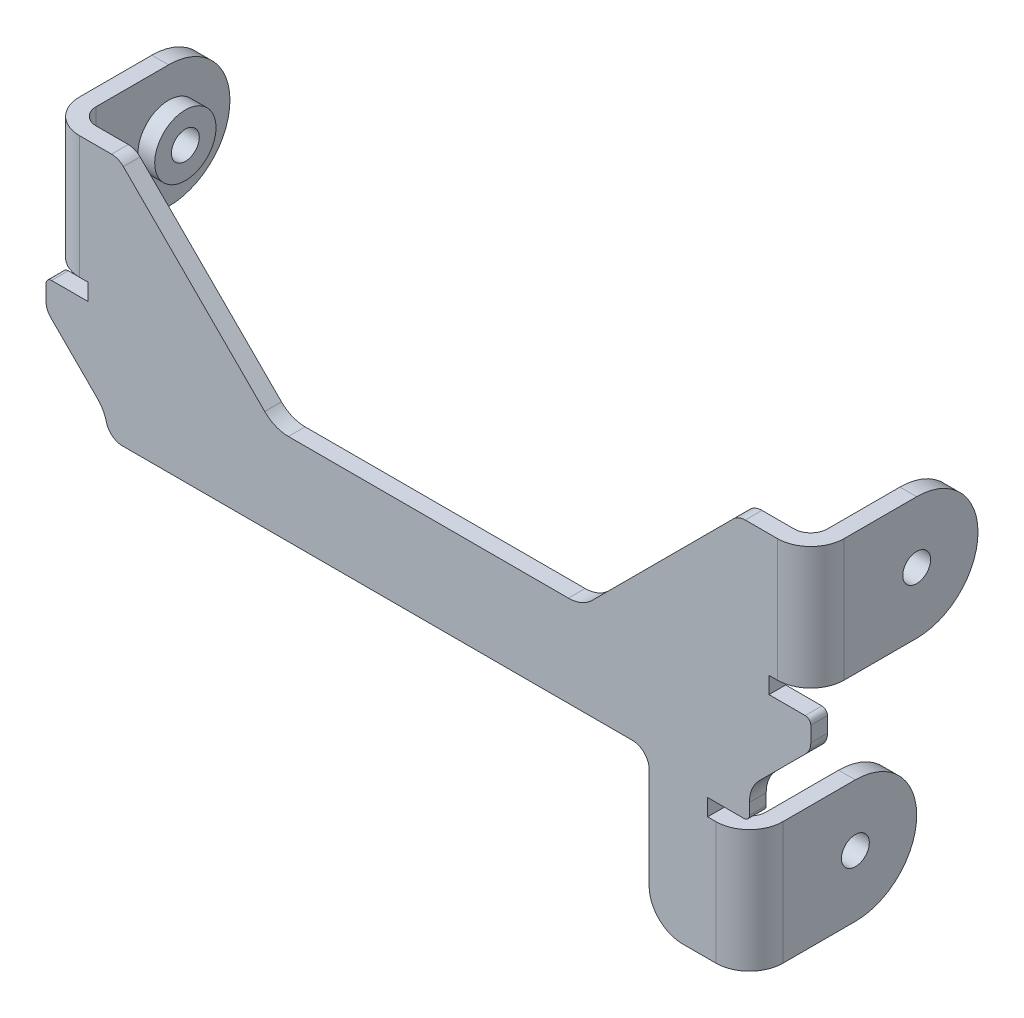
SolidWorks part; units mm, degrees
ref_plane "前视基准面" through (0, 0, 0) normal (0, 0, 1) x (1, 0, 0)
ref_plane "上视基准面" through (0, 0, 0) normal (0, 1, 0) x (1, 0, 0)
ref_plane "右视基准面" through (0, 0, 0) normal (1, 0, 0) x (0, 0, -1)
sketch "草图1" plane through (0, 0, 0) normal (0, 0, 1) x (1, 0, 0)
  line L0 (-11.75, 37) -> (-11.75, 24.7574)
  line L1 (-11.75, 24.7574) -> (-6.25, 24.7574)
  line L2 (-6.25, 24.7574) -> (-6.25, 37)
  line L3 (-6.25, 37) -> (-11.75, 37)
extrude "凸台-拉伸1" add sketch "草图1" against normal blind 1.5
sketch "草图2" plane through (-11.75, 0, 0) normal (-1, 0, 0) x (0, 0, 1)
  line L0 (0, 37) -> (0, 12.2574)
  line L1 (0, 12.2574) -> (-1.5, 12.2574)
  line L2 (-1.5, 12.2574) -> (-1.5, 37)
  line L3 (-1.5, 37) -> (0, 37)
extrude "凸台-拉伸2" add sketch "草图2" along normal blind 55.6
sketch "草图3" plane through (-11.75, 0, 0) normal (1, 0, 0) x (0, 0, -1)
  line L0 (0, 23.2574) -> (1.5, 23.2574)
  line L1 (1.5, 23.2574) -> (1.5, 12.2574)
  line L2 (1.5, 12.2574) -> (0, 12.2574)
  line L3 (0, 12.2574) -> (0, 23.2574)
extrude "凸台-拉伸3" add sketch "草图3" along normal blind 2.25
sketch "草图4" plane through (0, 37, 0) normal (0, 1, 0) x (-1, 0, 0)
  line L0 (4, 0) -> (67.35, 0)
  line L1 (67.35, 0) -> (67.35, -1.5)
  line L2 (67.35, -1.5) -> (4, -1.5)
  line L3 (4, -1.5) -> (4, 0)
extrude "凸台-拉伸4" add sketch "草图4" along normal blind 11
sketch "草图5" plane through (-4, 0, 0) normal (1, 0, 0) x (0, 0, -1)
  line L0 (0, 48) -> (9.5, 48)
  line L1 (9.5, 37) -> (0, 37)
  line L2 (0, 37) -> (0, 48)
  arc A0 (9.5, 48) -> (9.5, 37) centre (9.5, 42.5) cw
extrude "凸台-拉伸5" add sketch "草图5" along normal blind 1.5
sketch "草图6" plane through (-9.5, 0, 0) normal (1, 0, 0) x (0, 0, -1)
  line L0 (9.5, 12.2574) -> (0, 12.2574)
  line L1 (0, 12.2574) -> (0, 23.2574)
  line L2 (0, 23.2574) -> (9.5, 23.2574)
  arc A0 (9.5, 23.2574) -> (9.5, 12.2574) centre (9.5, 17.7574) cw
extrude "凸台-拉伸6" add sketch "草图6" along normal blind 1.5
sketch "草图7" plane through (-67.35, 0, 0) normal (-1, 0, 0) x (0, 0, 1)
  line L0 (0, 37) -> (-1.5, 37)
  line L1 (-1.5, 37) -> (-1.5, 48)
  line L2 (-1.5, 48) -> (0, 48)
  line L3 (0, 48) -> (0, 37)
extrude "凸台-拉伸7" add sketch "草图7" along normal blind 2.25
sketch "草图8" plane through (-69.6, 0, 0) normal (-1, 0, 0) x (0, 0, 1)
  line L0 (-9.5, 48) -> (0, 48)
  line L1 (0, 48) -> (0, 37)
  line L2 (0, 37) -> (-9.5, 37)
  arc A0 (-9.5, 37) -> (-9.5, 48) centre (-9.5, 42.5) cw
extrude "凸台-拉伸8" add sketch "草图8" along normal blind 1.5
sketch "草图9" plane through (-67.35, 0, 0) normal (-1, 0, 0) x (0, 0, 1)
  line L0 (-1.5, 12.2574) -> (-1.5, 35.5)
  line L1 (-1.5, 35.5) -> (0, 35.5)
  line L2 (0, 35.5) -> (0, 12.2574)
  line L3 (0, 12.2574) -> (-1.5, 12.2574)
extrude "凸台-拉伸9" add sketch "草图9" along normal blind 3.75
sketch "草图10" plane through (-6.25, 0, 0) normal (1, 0, 0) x (0, 0, -1)
  line L0 (0, 24.7574) -> (0, 35.5)
  line L1 (0, 35.5) -> (1.5, 35.5)
  line L2 (1.5, 35.5) -> (1.5, 24.7574)
  line L3 (1.5, 24.7574) -> (0, 24.7574)
extrude "凸台-拉伸10" add sketch "草图10" along normal blind 3.75
sketch "草图11" plane through (0, 0, -1.5) normal (0, 0, -1) x (-1, 0, 0)
  line L0 (71.1, 25.8229) -> (17, 25.8229)
  line L1 (17, 25.8229) -> (17, 12.2574)
  line L2 (17, 12.2574) -> (71.1, 12.2574)
  line L3 (71.1, 12.2574) -> (71.1, 25.8229)
extrude "切除-拉伸1" cut sketch "草图11" against normal through all
sketch "草图12" plane through (0, 0, 0) normal (0, 0, 1) x (1, 0, 0)
  line L0 (-71.1, 25.8229) -> (-65.6316, 25.8229)
  line L1 (-66.4787, 28.3787) -> (-71.1, 33)
  line L2 (-71.1, 33) -> (-71.1, 25.8229)
  arc A0 (-65.6316, 25.8229) -> (-66.4787, 28.3787) centre (-68.6, 26.2574) ccw
extrude "切除-拉伸2" cut sketch "草图12" against normal through all
sketch "草图13" plane through (0, 0, -1.5) normal (0, 0, -1) x (-1, 0, 0)
  line L0 (8, 24.7574) -> (8, 27.5)
  line L1 (8, 27.5) -> (2.5, 33)
  line L2 (2.5, 33) -> (2.5, 24.7574)
  line L3 (2.5, 24.7574) -> (8, 24.7574)
extrude "切除-拉伸3" cut sketch "草图13" against normal through all
sketch "草图14" plane through (0, 0, -1.5) normal (0, 0, -1) x (-1, 0, 0)
  line L0 (64.6, 48) -> (9, 48)
  line L1 (9, 48) -> (23, 34)
  line L2 (23, 34) -> (50.6, 34)
  line L3 (50.6, 34) -> (64.6, 48)
extrude "切除-拉伸4" cut sketch "草图14" against normal through all
ref_plane "基准面1" through (0, 0, -9.5) normal (0, 0, 1) x (1, 0, 0)
sketch "草图15" plane through (0, 0, -9.5) normal (0, 0, 1) x (1, 0, 0)
  line L0 (-11, 20.5074) -> (-11, 17.7574)
  line L1 (-11, 17.7574) -> (-9.5, 17.7574)
  line L2 (-9.5, 17.7574) -> (-9.5, 20.5074)
  line L3 (-9.5, 20.5074) -> (-11, 20.5074)
  line L4 (-11, 17.7574) -> (-9.5, 17.7574) construction
revolve "旋转1" add sketch "草图15" angle 360 about L4
sketch "草图16" plane through (0, 0, -9.5) normal (0, 0, 1) x (1, 0, 0)
  line L0 (-5.5, 45.25) -> (-5.5, 42.5)
  line L1 (-5.5, 42.5) -> (-4, 42.5)
  line L2 (-4, 42.5) -> (-4, 45.25)
  line L3 (-4, 45.25) -> (-5.5, 45.25)
  line L4 (-5.5, 42.5) -> (-4, 42.5) construction
revolve "旋转2" add sketch "草图16" angle 360 about L4
ref_plane "基准面2" through (0, 0, -9.5) normal (0, 0, -1) x (-1, 0, 0)
sketch "草图17" plane through (0, 0, -9.5) normal (0, 0, -1) x (-1, 0, 0)
  line L0 (68.1, 45.25) -> (68.1, 42.5)
  line L1 (68.1, 42.5) -> (69.6, 42.5)
  line L2 (69.6, 42.5) -> (69.6, 45.25)
  line L3 (69.6, 45.25) -> (68.1, 45.25)
  line L4 (68.1, 42.5) -> (69.6, 42.5) construction
revolve "旋转3" add sketch "草图17" angle 360 about L4
hole_wizard "Ø2.5 (2.5) 直径孔1" positions "草图19" profile "草图18" hole size "Ø2.5" standard "ANSI Metric"
sketch "草图19" plane through (-8, 0, 0) normal (1, 0, 0) x (0, 0, -1)
  point P0 (9.5, 17.7574)
sketch "草图18" plane through (-8, 17.7574, -9.5) normal (0, 1, 0) x (0, 0, -1)
  line L0 (0, 0) -> (0, 63.1)
  line L1 (0, 63.1) -> (1.25, 63.1)
  line L2 (1.25, 63.1) -> (1.25, 0)
  line L5 (1.25, 0) -> (0, 0)
  line L11 (0, -6.35) -> (0, 107.95) construction
  dimension "通孔孔直径" = 2.5
  dimension "通孔孔深度" = 63.1
hole_wizard "Ø2.5 (2.5) 直径孔2" positions "草图21" profile "草图20" hole size "Ø2.5" standard "ANSI Metric"
sketch "草图21" plane through (-2.5, 0, 0) normal (1, 0, 0) x (0, 0, -1)
  point P0 (9.5, 42.5)
sketch "草图20" plane through (-2.5, 42.5, -9.5) normal (0, 1, 0) x (0, 0, -1)
  line L0 (0, 0) -> (0, 3)
  line L1 (0, 3) -> (1.25, 3)
  line L2 (1.25, 3) -> (1.25, 0)
  line L5 (1.25, 0) -> (0, 0)
  line L11 (0, -6.35) -> (0, 107.95) construction
  dimension "通孔孔直径" = 2.5
  dimension "通孔孔深度" = 3
hole_wizard "Ø2.5 (2.5) 直径孔3" positions "草图23" profile "草图22" hole size "Ø2.5" standard "ANSI Metric"
sketch "草图23" plane through (-71.1, 0, 0) normal (-1, 0, 0) x (0, 0, 1)
  point P0 (-9.5, 42.5)
sketch "草图22" plane through (-71.1, 42.5, -9.5) normal (0, 1, 0) x (0, 0, 1)
  line L0 (0, 0) -> (0, 68.6)
  line L1 (0, 68.6) -> (1.25, 68.6)
  line L2 (1.25, 68.6) -> (1.25, 0)
  line L5 (1.25, 0) -> (0, 0)
  line L11 (0, -6.35) -> (0, 107.95) construction
  dimension "通孔孔直径" = 2.5
  dimension "通孔孔深度" = 68.6
fillet "圆角1" radius 0.5 3 edges at (-71.1, 35.5, -0.75) (-8, 24.7574, -0.75) (-2.5, 35.5, -0.75)
fillet "圆角2" radius 1.5 9 edges at (-2.5, 33, -0.75) (-65.6316, 25.8229, -0.75) (-4, 42.5, -1.5) (-9.5, 17.7574, -1.5) (-17, 25.8229, -0.75) (-69.6, 42.5, -1.5) (-71.1, 33, -0.75) (-9, 48, -0.75) (-64.6, 48, -0.75)
fillet "圆角3" radius 3 7 edges at (-71.1, 42.5, 0) (-23, 34, -0.75) (-50.6, 34, -0.75) (-8, 27.5, -0.75) (-17, 12.2574, -0.75) (-8, 17.7574, 0) (-2.5, 42.5, 0)
